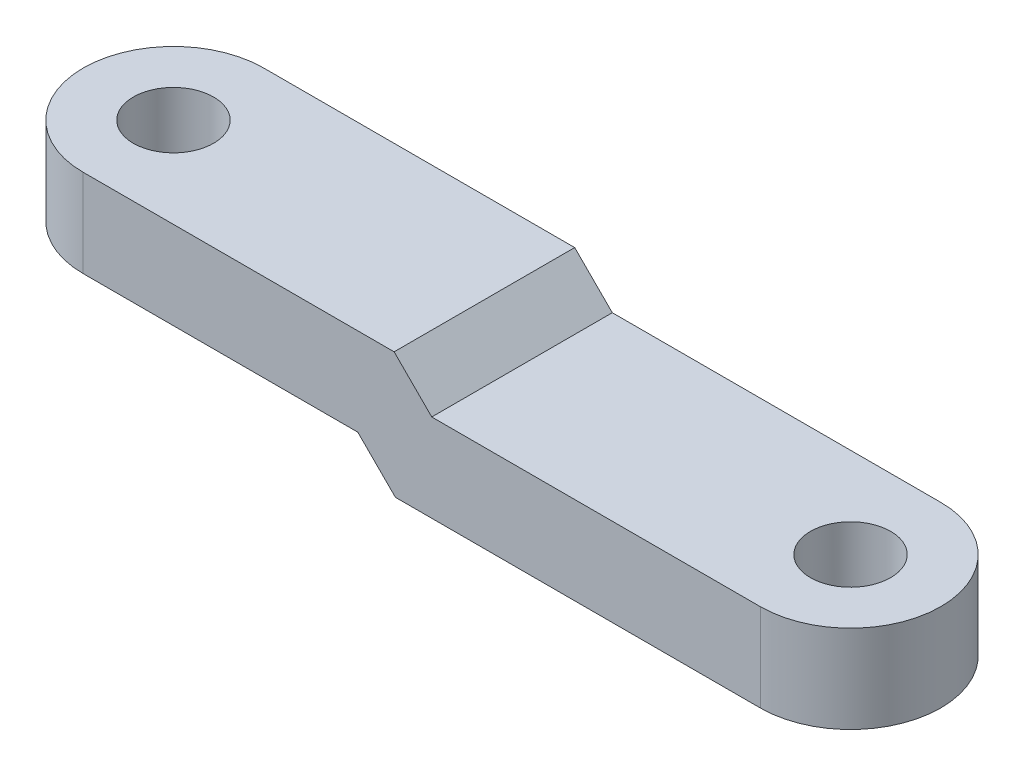
SolidWorks part; units mm, degrees
ref_plane "Front Plane" through (0, 0, 0) normal (0, 0, 1) x (1, 0, 0)
ref_plane "Top Plane" through (0, 0, 0) normal (0, 1, 0) x (1, 0, 0)
ref_plane "Right Plane" through (0, 0, 0) normal (1, 0, 0) x (0, 0, -1)
sketch "Sketch1" plane through (0, 0, 0) normal (0, 1, 0) x (1, 0, 0)
  line L0 (-27, 3.6) -> (0, 3.6)
  line L1 (-27, -3.6) -> (0, -3.6)
  circle A0 centre (0, 0) radius 1.6
  circle A1 centre (-27, 0) radius 1.6
  arc A2 (-27, 3.6) -> (-27, -3.6) centre (-27, 0) ccw
  arc A3 (0, -3.6) -> (0, 3.6) centre (0, 0) ccw
  circle A4 centre (-27, 0) radius 3.6 construction
  circle A5 centre (0, 0) radius 3.6 construction
  dimension "D1" = 3.2
  dimension "D2" = 3.2
  dimension "D3" = 27
  dimension "D4" = 2
extrude "Boss-Extrude1" add sketch "Sketch1" along normal blind 5
sketch "Sketch2" plane through (0, 0, 3.6) normal (0, 0, 1) x (1, 0, 0)
  line L0 (-30.6, 5) -> (-14.6, 5)
  line L1 (-27, 5) -> (0, 5) construction
  line L2 (-14.6, 5) -> (-13.1, 3.5)
  line L3 (-13.1, 3.5) -> (3.6, 3.5)
  line L4 (3.6, 0) -> (3.6, 5) construction
  line L5 (3.6, 3.5) -> (3.6, 0)
  line L6 (3.6, 0) -> (-14.5497, 0)
  line L7 (-27, 0) -> (0, 0) construction
  line L8 (-14.5497, 0) -> (-16.0497, 1.5)
  line L9 (-16.0497, 1.5) -> (-30.6, 1.5)
  line L10 (-30.6, 5) -> (-30.6, 0) construction
  line L11 (-30.6, 1.5) -> (-30.6, 5)
  line L13 (-30.6, 5) -> (3.6, 5)
  line L14 (-30.6, 5) -> (-30.6, 0)
  line L15 (-30.6, 0) -> (3.6, 0)
  line L16 (3.6, 5) -> (3.6, 0)
  line M9 (-27, 0) -> (0, 0)
  line M10 (0, 0) -> (0, 5)
  line M11 (0, 5) -> (-27, 5)
  line M12 (-27, 5) -> (-27, 0)
  dimension "D1" = 16
  dimension "D2" = 135
  dimension "D3" = 3.5
  dimension "D4" = 3.5
  dimension "D5" = 3.5
extrude "Cut-Extrude1" cut sketch "Sketch2" against normal through all contours L8 L9 M12 M9 | L14 L15 L9 M12 | L2 L3 M10 M11 | L16 L13 L3 M10
